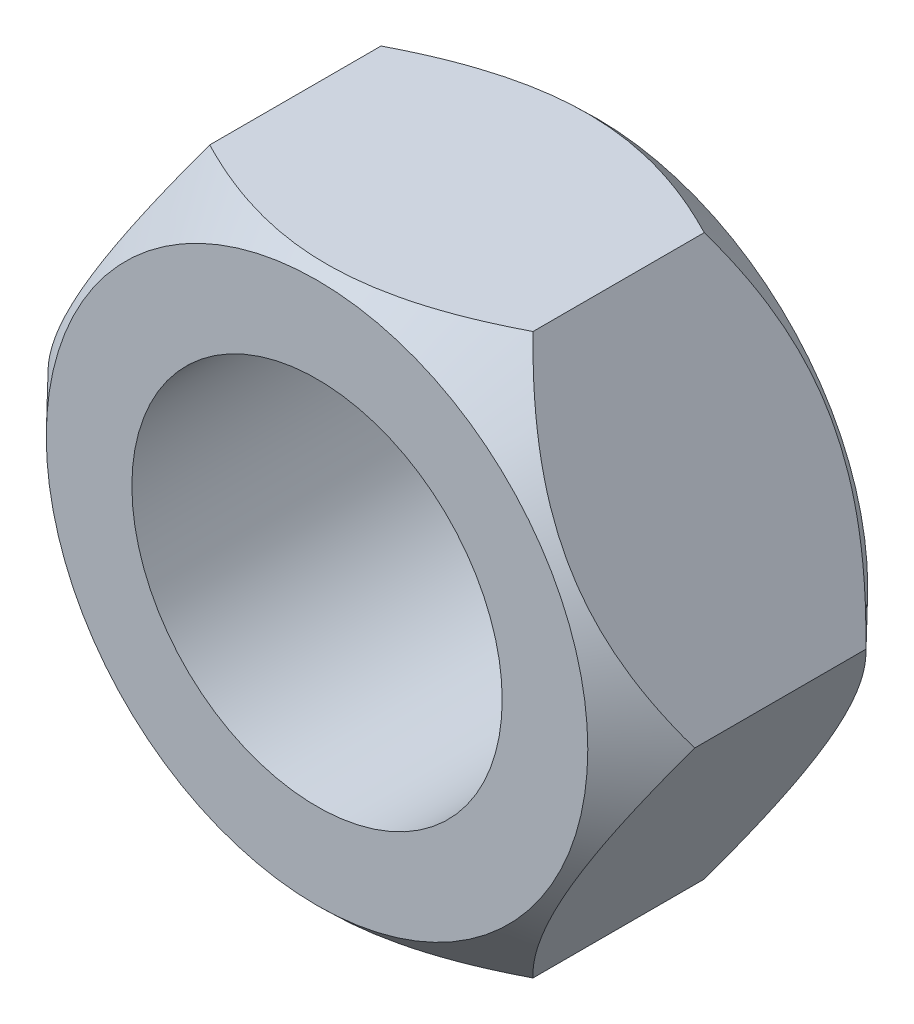
SolidWorks part; units mm, degrees
ref_plane "Alzado" through (0, 0, 0) normal (0, 0, 1) x (1, 0, 0)
ref_plane "Planta" through (0, 0, 0) normal (0, 1, 0) x (1, 0, 0)
ref_plane "Vista lateral" through (0, 0, 0) normal (1, 0, 0) x (0, 0, -1)
sketch "Croquis1" plane through (0, 0, 0) normal (0, 0, 1) x (1, 0, 0)
  line L1 (13.8564, 0) -> (6.9282, 12)
  line L2 (6.9282, 12) -> (-6.9282, 12)
  line L3 (-6.9282, 12) -> (-13.8564, 0)
  line L4 (-13.8564, 0) -> (-6.9282, -12)
  line L5 (-6.9282, -12) -> (6.9282, -12)
  line L6 (6.9282, -12) -> (13.8564, 0)
  circle A0 centre (0, 0) radius 12 construction
  circle A1 centre (0, 0) radius 7.9375
  dimension "D2" = 15.875
  dimension "D1" = 24
extrude "Saliente-Extruir1" add sketch "Croquis1" along normal blind 12
sketch "Croquis2" plane through (0, 0, 12) normal (0, 0, 1) x (1, 0, 0)
  circle A0 centre (0, 0) radius 11.6072
  circle A1 centre (0, 0) radius 26.0208
extrude "Cortar-Extruir1" cut sketch "Croquis2" against normal blind 11 draft 44
sketch "Croquis3" plane through (0, 0, 0) normal (0, 0, -1) x (-1, 0, 0)
  circle A0 centre (0, 0) radius 11.6072
  circle A1 centre (0, 0) radius 34.2664
extrude "Cortar-Extruir2" cut sketch "Croquis3" against normal blind 11 draft 44
